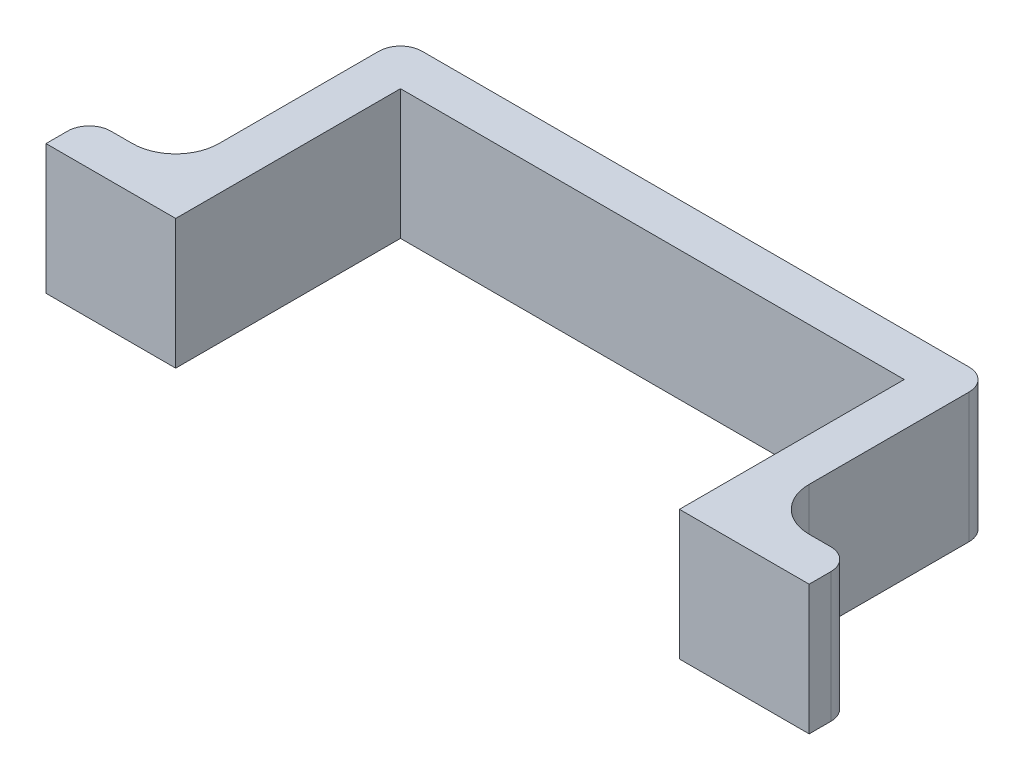
SolidWorks part; units mm, degrees
ref_plane "Front Plane" through (0, 0, 0) normal (0, 0, 1) x (1, 0, 0)
ref_plane "Top Plane" through (0, 0, 0) normal (0, 1, 0) x (1, 0, 0)
ref_plane "Right Plane" through (0, 0, 0) normal (1, 0, 0) x (0, 0, -1)
sketch "Sketch1" plane through (0, 0, 0) normal (0, 1, 0) x (1, 0, 0)
  line L0 (0, 0) -> (0, -85.5367) construction
  line L5 (-37, 0) -> (37, 0)
  line L7 (-40.175, 6.35) -> (40.175, 6.35)
  line L8 (43.35, 0) -> (43.35, 3.175)
  line L10 (43.35, 0) -> (43.35, -20.32)
  line L11 (30.65, -33.02) -> (37, -33.02)
  line L12 (37, 0) -> (37, -33.02)
  line L13 (30.65, -33.02) -> (56.05, -33.02)
  line L15 (49.7, -26.67) -> (52.875, -26.67)
  line L16 (56.05, -33.02) -> (56.05, -29.845)
  line L17 (-43.35, 0) -> (-43.35, -20.32)
  line L18 (-49.7, -26.67) -> (-52.875, -26.67)
  line L19 (-56.05, -33.02) -> (-56.05, -29.845)
  line L20 (-30.65, -33.02) -> (-56.05, -33.02)
  line L21 (-30.65, -33.02) -> (-37, -33.02)
  line L22 (-37, 0) -> (-37, -33.02)
  line L23 (-43.35, 0) -> (-43.35, 3.175)
  arc A0 (43.35, -20.32) -> (49.7, -26.67) centre (49.7, -20.32) ccw
  arc A1 (-43.35, -20.32) -> (-49.7, -26.67) centre (-49.7, -20.32) cw
  arc A2 (52.875, -26.67) -> (56.05, -29.845) centre (52.875, -29.845) cw
  arc A3 (-52.875, -26.67) -> (-56.05, -29.845) centre (-52.875, -29.845) ccw
  arc A4 (40.175, 6.35) -> (43.35, 3.175) centre (40.175, 3.175) cw
  arc A5 (-43.35, 3.175) -> (-40.175, 6.35) centre (-40.175, 3.175) cw
  point P24 (43.35, -26.67)
  point P27 (-43.35, -26.67)
  point P30 (56.05, -26.67)
  point P33 (-56.05, -26.67)
  point P36 (43.35, 6.35)
  point P39 (-43.35, 6.35)
  dimension "D7" = 6.35
  dimension "D8" = 3.175
  dimension "D9" = 3.175
  dimension "D1" = 33.02
  dimension "D2" = 6.35
  dimension "D4" = 6.35
  dimension "D5" = 12.7
  dimension "D6" = 37
extrude "Boss-Extrude1" add sketch "Sketch1" along normal blind 19.05
